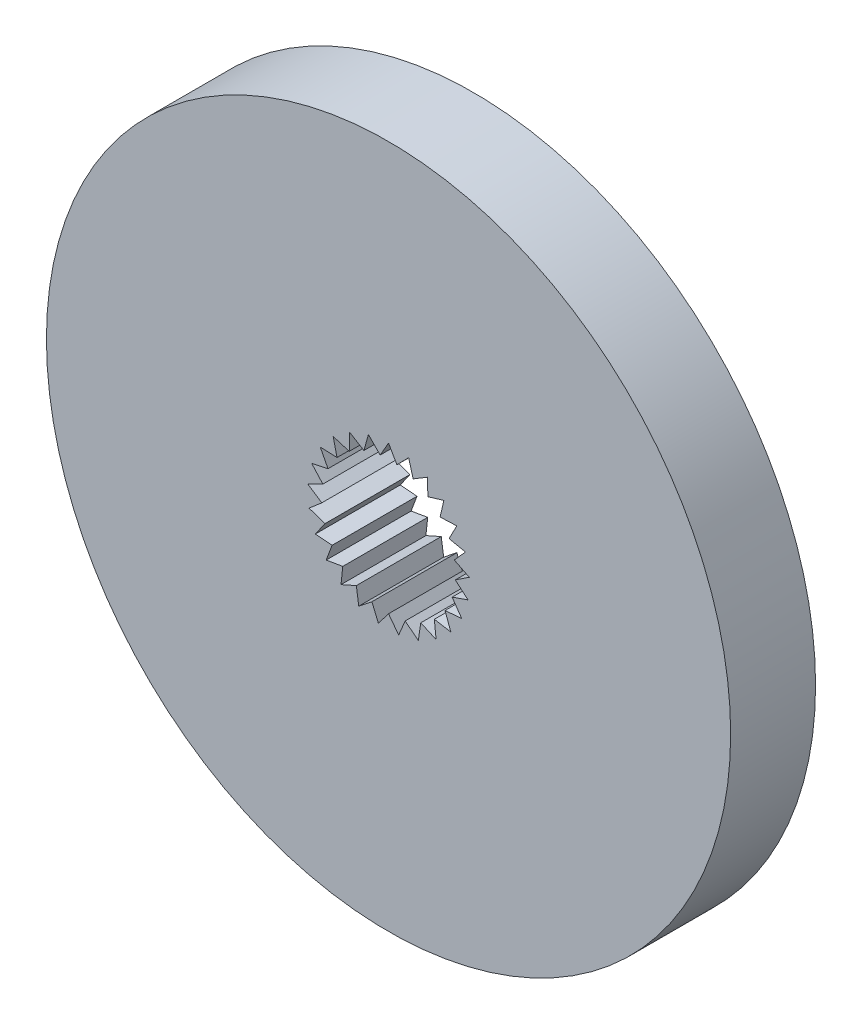
SolidWorks part; units mm, degrees
ref_plane "Front Plane" through (0, 0, 0) normal (0, 0, 1) x (1, 0, 0)
ref_plane "Top Plane" through (0, 0, 0) normal (0, 1, 0) x (1, 0, 0)
ref_plane "Right Plane" through (0, 0, 0) normal (1, 0, 0) x (0, 0, -1)
sketch "Sketch1" plane through (0, 0, 0) normal (0, 0, 1) x (1, 0, 0)
  line L0 (0, 3.048) -> (0, 0) construction
  line L1 (0, 3.048) -> (-0.3159, 2.5008)
  line L2 (0, 3.048) -> (0.3159, 2.5008)
  line L3 (-0.3159, 2.5008) -> (0.3159, 2.5008) construction
  line L4 (0.758, 2.9522) -> (0.3159, 2.5008)
  line L5 (0.758, 2.9522) -> (0.9279, 2.3437)
  line L6 (0.3159, 2.5008) -> (0.9279, 2.3437) construction
  line L7 (1.4684, 2.671) -> (0.9279, 2.3437)
  line L8 (1.4684, 2.671) -> (1.4816, 2.0393)
  line L9 (0.9279, 2.3437) -> (1.4816, 2.0393) construction
  line L10 (2.0865, 2.2219) -> (1.4816, 2.0393)
  line L11 (2.0865, 2.2219) -> (1.9422, 1.6067)
  line L12 (1.4816, 2.0393) -> (1.9422, 1.6067) construction
  line L13 (2.5735, 1.6332) -> (1.9422, 1.6067)
  line L14 (2.5735, 1.6332) -> (2.2808, 1.0733)
  line L15 (1.9422, 1.6067) -> (2.2808, 1.0733) construction
  line L16 (2.8988, 0.9419) -> (2.2808, 1.0733)
  line L17 (2.8988, 0.9419) -> (2.476, 0.4723)
  line L18 (2.2808, 1.0733) -> (2.476, 0.4723) construction
  line L19 (3.042, 0.1914) -> (2.476, 0.4723)
  line L20 (3.042, 0.1914) -> (2.5157, -0.1583)
  line L21 (2.476, 0.4723) -> (2.5157, -0.1583) construction
  line L22 (2.994, -0.5711) -> (2.5157, -0.1583)
  line L23 (2.994, -0.5711) -> (2.3973, -0.7789)
  line L24 (2.5157, -0.1583) -> (2.3973, -0.7789) construction
  line L25 (2.7579, -1.2978) -> (2.3973, -0.7789)
  line L26 (2.7579, -1.2978) -> (2.1283, -1.3506)
  line L27 (2.3973, -0.7789) -> (2.1283, -1.3506) construction
  line L28 (2.3485, -1.9429) -> (2.1283, -1.3506)
  line L29 (2.3485, -1.9429) -> (1.7255, -1.8375)
  line L30 (2.1283, -1.3506) -> (1.7255, -1.8375) construction
  line L31 (1.7916, -2.4659) -> (1.7255, -1.8375)
  line L32 (1.7916, -2.4659) -> (1.2143, -2.2089)
  line L33 (1.7255, -1.8375) -> (1.2143, -2.2089) construction
  line L34 (1.122, -2.834) -> (1.2143, -2.2089)
  line L35 (1.122, -2.834) -> (0.6269, -2.4415)
  line L36 (1.2143, -2.2089) -> (0.6269, -2.4415) construction
  line L37 (0.382, -3.024) -> (0.6269, -2.4415)
  line L38 (0.382, -3.024) -> (0, -2.5207)
  line L39 (0.6269, -2.4415) -> (0, -2.5207) construction
  line L40 (-0.382, -3.024) -> (0, -2.5207)
  line L41 (-0.382, -3.024) -> (-0.6269, -2.4415)
  line L42 (0, -2.5207) -> (-0.6269, -2.4415) construction
  line L43 (-1.122, -2.834) -> (-0.6269, -2.4415)
  line L44 (-1.122, -2.834) -> (-1.2143, -2.2089)
  line L45 (-0.6269, -2.4415) -> (-1.2143, -2.2089) construction
  line L46 (-1.7916, -2.4659) -> (-1.2143, -2.2089)
  line L47 (-1.7916, -2.4659) -> (-1.7255, -1.8375)
  line L48 (-1.2143, -2.2089) -> (-1.7255, -1.8375) construction
  line L49 (-2.3485, -1.9429) -> (-1.7255, -1.8375)
  line L50 (-2.3485, -1.9429) -> (-2.1283, -1.3506)
  line L51 (-1.7255, -1.8375) -> (-2.1283, -1.3506) construction
  line L52 (-2.7579, -1.2978) -> (-2.1283, -1.3506)
  line L53 (-2.7579, -1.2978) -> (-2.3973, -0.7789)
  line L54 (-2.1283, -1.3506) -> (-2.3973, -0.7789) construction
  line L55 (-2.994, -0.5711) -> (-2.3973, -0.7789)
  line L56 (-2.994, -0.5711) -> (-2.5157, -0.1583)
  line L57 (-2.3973, -0.7789) -> (-2.5157, -0.1583) construction
  line L58 (-3.042, 0.1914) -> (-2.5157, -0.1583)
  line L59 (-3.042, 0.1914) -> (-2.476, 0.4723)
  line L60 (-2.5157, -0.1583) -> (-2.476, 0.4723) construction
  line L61 (-2.8988, 0.9419) -> (-2.476, 0.4723)
  line L62 (-2.8988, 0.9419) -> (-2.2808, 1.0733)
  line L63 (-2.476, 0.4723) -> (-2.2808, 1.0733) construction
  line L64 (-2.5735, 1.6332) -> (-2.2808, 1.0733)
  line L65 (-2.5735, 1.6332) -> (-1.9422, 1.6067)
  line L66 (-2.2808, 1.0733) -> (-1.9422, 1.6067) construction
  line L67 (-2.0865, 2.2219) -> (-1.9422, 1.6067)
  line L68 (-2.0865, 2.2219) -> (-1.4816, 2.0393)
  line L69 (-1.9422, 1.6067) -> (-1.4816, 2.0393) construction
  line L70 (-1.4684, 2.671) -> (-1.4816, 2.0393)
  line L71 (-1.4684, 2.671) -> (-0.9279, 2.3437)
  line L72 (-1.4816, 2.0393) -> (-0.9279, 2.3437) construction
  line L73 (-0.758, 2.9522) -> (-0.9279, 2.3437)
  line L74 (-0.758, 2.9522) -> (-0.3159, 2.5008)
  line L75 (-0.9279, 2.3437) -> (-0.3159, 2.5008) construction
  circle A1 centre (0, 0) radius 12.8934
  point P0 (0, 2.5008)
  point P12 (0.6219, 2.4222)
  point P16 (1.2048, 2.1915)
  point P20 (1.7119, 1.823)
  point P24 (2.1115, 1.34)
  point P28 (2.3784, 0.7728)
  point P32 (2.4959, 0.157)
  point P36 (2.4565, -0.4686)
  point P40 (2.2628, -1.0648)
  point P44 (1.9269, -1.5941)
  point P48 (1.4699, -2.0232)
  point P52 (0.9206, -2.3252)
  point P56 (0.3134, -2.4811)
  point P60 (-0.3134, -2.4811)
  point P64 (-0.9206, -2.3252)
  point P68 (-1.4699, -2.0232)
  point P72 (-1.9269, -1.5941)
  point P76 (-2.2628, -1.0648)
  point P80 (-2.4565, -0.4686)
  point P84 (-2.4959, 0.157)
  point P88 (-2.3784, 0.7728)
  point P92 (-2.1115, 1.34)
  point P96 (-1.7119, 1.823)
  point P100 (-1.2048, 2.1915)
  point P104 (-0.6219, 2.4222)
  dimension "D1" = 25
  dimension "D3" = 25.7868
  dimension "D2" = 60
extrude "Boss-Extrude1" add sketch "Sketch1" along normal blind 3.2004
